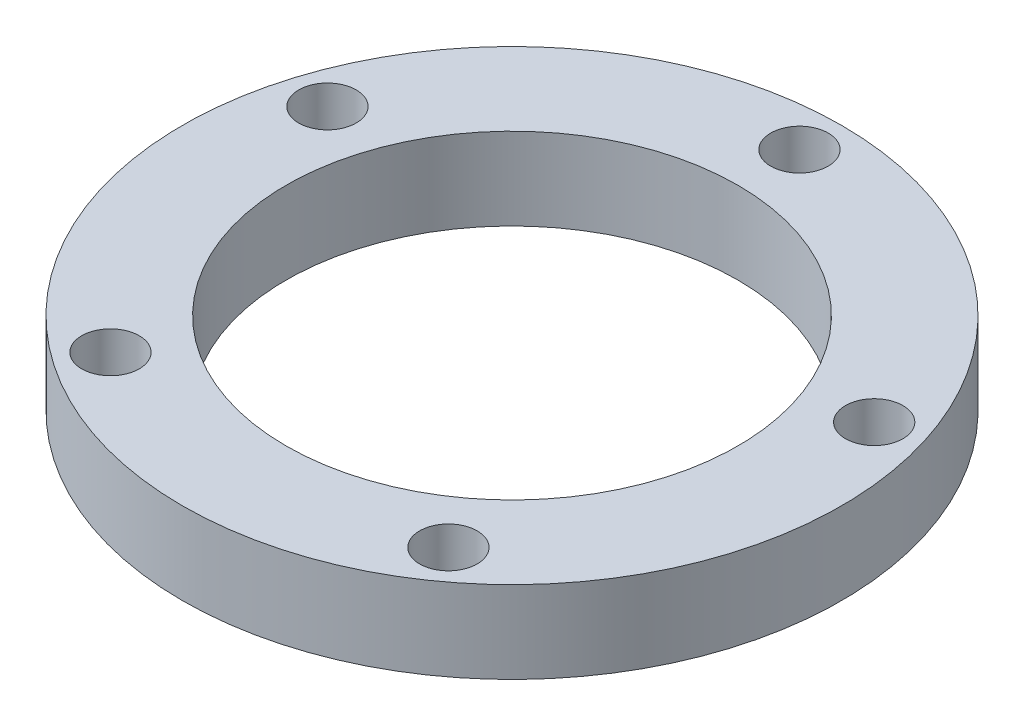
SolidWorks part; units mm, degrees
ref_plane "Front Plane" through (0, 0, 0) normal (0, 0, 1) x (1, 0, 0)
ref_plane "Top Plane" through (0, 0, 0) normal (0, 1, 0) x (1, 0, 0)
ref_plane "Right Plane" through (0, 0, 0) normal (1, 0, 0) x (0, 0, -1)
sketch "Sketch1" plane through (0, 0, 0) normal (0, 1, 0) x (1, 0, 0)
  circle A0 centre (0, 0) radius 40.125
  dimension "D1" = 80.25
extrude "Boss-Extrude1" add sketch "Sketch1" along normal blind 10
sketch "Sketch2" plane through (0, 10, 0) normal (0, 1, 0) x (1, 0, 0)
  circle A0 centre (0, 0) radius 27.5
  dimension "D1" = 55
extrude "Cut-Extrude1" cut sketch "Sketch2" against normal blind 10
sketch "Sketch3" plane through (0, 10, 0) normal (0, 1, 0) x (1, 0, 0)
  line L0 (0, 0) -> (0, 35) construction
  circle A0 centre (0, 35) radius 3.5
  circle A1 centre (33.287, 10.8156) radius 3.5
  circle A2 centre (20.5725, -28.3156) radius 3.5
  circle A3 centre (-20.5725, -28.3156) radius 3.5
  circle A4 centre (-33.287, 10.8156) radius 3.5
  point P14 (0, 0)
  dimension "D1" = 7
  dimension "D2" = 35
  dimension "D3" = 5
extrude "Cut-Extrude2" cut sketch "Sketch3" against normal blind 10
sketch "Sketch4" plane through (0, 0, 0) normal (0, -1, 0) x (1, 0, 0)
  circle A0 centre (0, -35) radius 7
  circle A1 centre (-33.287, -10.8156) radius 7
  circle A2 centre (-20.5725, 28.3156) radius 7
  circle A3 centre (20.5725, 28.3156) radius 7
  circle A4 centre (33.287, -10.8156) radius 7
  point P13 (0, 0)
  dimension "D1" = 5
  dimension "5 mm" = 14
extrude "Cut-Extrude3" [suppressed] cut sketch "Sketch4" against normal blind 5
fillet "Fillet1" [suppressed] radius 5
